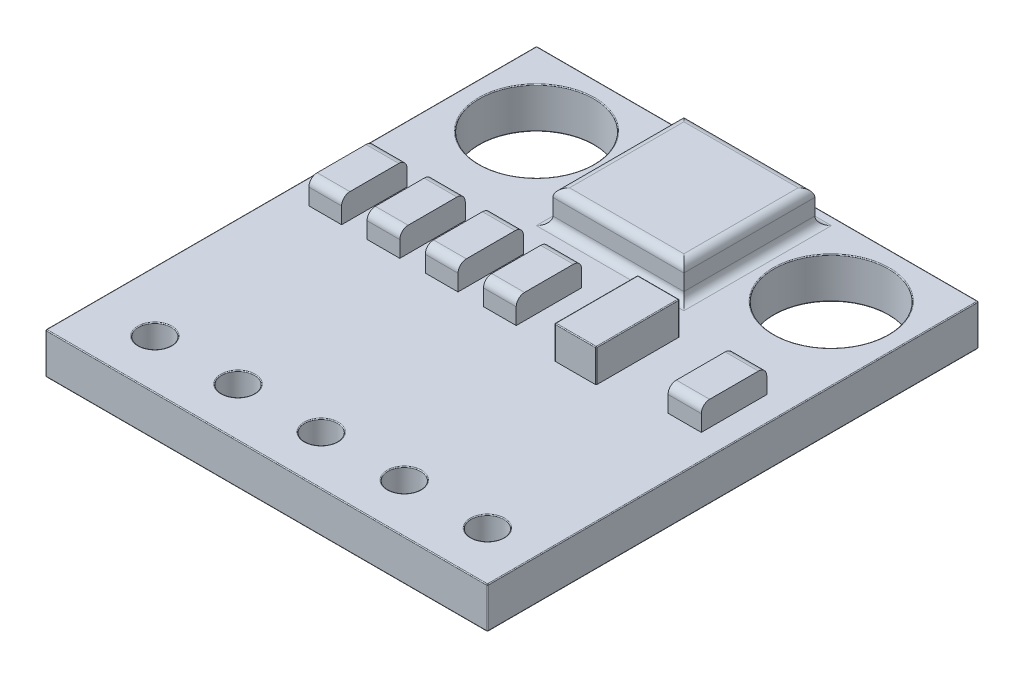
SolidWorks part; units mm, degrees
ref_plane "Front Plane" through (0, 0, 0) normal (0, 0, 1) x (1, 0, 0)
ref_plane "Top Plane" through (0, 0, 0) normal (0, 1, 0) x (1, 0, 0)
ref_plane "Right Plane" through (0, 0, 0) normal (1, 0, 0) x (0, 0, -1)
sketch "Sketch1" plane through (0, 0, 0) normal (0, 1, 0) x (1, 0, 0)
  line L1 (0, 0) -> (13.5, 0)
  line L2 (0, 0) -> (0, 15)
  line L3 (0, 15) -> (13.5, 15)
  line L4 (13.5, 0) -> (13.5, 15)
  dimension "D1" = 13.5
  dimension "D2" = 15
extrude "Boss-Extrude1" add sketch "Sketch1" along normal blind 1.25
sketch "Sketch2" plane through (0, 1.25, 0) normal (0, 1, 0) x (1, 0, 0)
  line L0 (0, 15) -> (0, 0) construction
  line L1 (5, 14.5) -> (9, 14.5)
  line L2 (5, 14.5) -> (5, 10.5)
  line L3 (5, 10.5) -> (9, 10.5)
  line L4 (9, 14.5) -> (9, 10.5)
  line L5 (13.5, 15) -> (0, 15) construction
  dimension "D1" = 4
  dimension "D2" = 4
  dimension "D3" = 5
  dimension "D4" = 0.5
extrude "Boss-Extrude2" add sketch "Sketch2" along normal blind 1
sketch "Sketch3" plane through (0, 1.25, 0) normal (0, 1, 0) x (1, 0, 0)
  line L0 (13.5, 0) -> (13.5, 15) construction
  line L1 (13.5, 15) -> (0, 15) construction
  line L2 (0, 15) -> (0, 0) construction
  circle A0 centre (11.25, 12.75) radius 1.75
  circle A1 centre (2.25, 12.75) radius 1.75
  dimension "D1" = 3.5
  dimension "D2" = 3.5
  dimension "D4" = 2.25
  dimension "D5" = 2.25
  dimension "D6" = 2.25
  dimension "D3" = 2.25
extrude "Cut-Extrude1" cut sketch "Sketch3" against normal blind 25.4
sketch "Sketch4" plane through (0, 1.25, 0) normal (0, 1, 0) x (1, 0, 0)
  line L0 (0, 15) -> (0, 0) construction
  line L1 (0.75, 9.2947) -> (1.75, 9.2947)
  line L2 (0.75, 9.2947) -> (0.75, 7.2947)
  line L3 (0.75, 7.2947) -> (1.75, 7.2947)
  line L4 (1.75, 9.2947) -> (1.75, 7.2947)
  line L5 (2.528, 9.2947) -> (3.528, 9.2947)
  line L6 (3.528, 9.2947) -> (3.528, 7.2947)
  line L7 (2.528, 7.2947) -> (3.528, 7.2947)
  line L8 (2.528, 9.2947) -> (2.528, 7.2947)
  line L9 (4.306, 9.2947) -> (5.306, 9.2947)
  line L10 (5.306, 9.2947) -> (5.306, 7.2947)
  line L11 (4.306, 7.2947) -> (5.306, 7.2947)
  line L12 (4.306, 9.2947) -> (4.306, 7.2947)
  line L13 (6.084, 9.2947) -> (7.084, 9.2947)
  line L14 (7.084, 9.2947) -> (7.084, 7.2947)
  line L15 (6.084, 7.2947) -> (7.084, 7.2947)
  line L16 (6.084, 9.2947) -> (6.084, 7.2947)
  line L17 (13.5, 0) -> (13.5, 15) construction
  line L18 (11.722, 9.2947) -> (12.738, 9.2947)
  line L19 (11.722, 9.2947) -> (11.722, 7.2947)
  line L20 (11.722, 7.2947) -> (12.738, 7.2947)
  line L21 (12.738, 9.2947) -> (12.738, 7.2947)
  dimension "D1" = 2
  dimension "D2" = 1
  dimension "D3" = 0.75
  dimension "D5" = 0.762
  dimension "D6" = 1.016
  dimension "D4" = 4
extrude "Boss-Extrude4" add sketch "Sketch4" along normal blind 0.75
sketch "Sketch5" plane through (0, 1.25, 0) normal (0, 1, 0) x (1, 0, 0)
  line L0 (7.084, 7.2947) -> (7.084, 9.2947) construction
  line L1 (8.608, 9.4836) -> (9.878, 9.4836)
  line L2 (8.608, 9.4836) -> (8.608, 6.9436)
  line L3 (8.608, 6.9436) -> (9.878, 6.9436)
  line L4 (9.878, 9.4836) -> (9.878, 6.9436)
  dimension "D1" = 1.27
  dimension "D2" = 2.54
  dimension "D3" = 1.524
extrude "Boss-Extrude5" add sketch "Sketch5" along normal blind 1
sketch "Sketch6" plane through (0, 1.25, 0) normal (0, 1, 0) x (1, 0, 0)
  line L0 (0, 0) -> (13.5, 0) construction
  line L1 (13.5, 0) -> (13.5, 15) construction
  circle A0 centre (12, 1.5) radius 0.5
  circle A1 centre (9.46, 1.5) radius 0.5
  circle A2 centre (6.92, 1.5) radius 0.5
  circle A3 centre (4.38, 1.5) radius 0.5
  circle A4 centre (1.84, 1.5) radius 0.5
  dimension "D1" = 1.5
  dimension "D2" = 1.5
  dimension "D3" = 5
extrude "Cut-Extrude2" cut sketch "Sketch6" against normal blind 25.4
fillet "Fillet1" radius 0.0254 4 edges at (11.25, 1.25, -11) (2.25, 1.25, -11) (11.25, 0, -14.5) (2.25, 0, -14.5)
fillet "Fillet2" radius 0.0254 10 edges at (1.84, 1.25, -1) (4.38, 1.25, -1) (6.92, 1.25, -1) (9.46, 1.25, -1) (12, 1.25, -1) (1.84, 0, -2) (4.38, 0, -2) (6.92, 0, -2) (9.46, 0, -2) (12, 0, -2)
fillet "Fillet3" radius 0.254 10 edges at (12.23, 2, -9.2947) (12.23, 2, -7.2947) (6.584, 2, -7.2947) (6.584, 2, -9.2947) (3.028, 2, -9.2947) (4.806, 2, -9.2947) (4.806, 2, -7.2947) (3.028, 2, -7.2947) (1.25, 2, -9.2947) (1.25, 2, -7.2947)
fillet "Fillet4" radius 0.254 8 edges at (9, 2.25, -12.5) (7, 2.25, -14.5) (5, 2.25, -12.5) (7, 2.25, -10.5) (7, 1.25, -10.5) (5, 1.25, -12.5) (7, 1.25, -14.5) (9, 1.25, -12.5)
fillet "Fillet5" radius 0.0254 8 edges at (8.608, 1.75, -6.9436) (8.608, 1.75, -9.4836) (9.878, 1.75, -9.4836) (9.878, 1.75, -6.9436) (9.243, 2.25, -9.4836) (8.608, 2.25, -8.2136) (9.243, 2.25, -6.9436) (9.878, 2.25, -8.2136)
fillet "Fillet6" radius 0.0254 12 edges at (6.75, 1.25, -15) (6.75, 0, -15) (0, 0.625, -15) (0, 1.25, -7.5) (0, 0, -7.5) (0, 0.625, 0) (6.75, 1.25, 0) (6.75, 0, 0) (13.5, 0.625, 0) (13.5, 1.25, -7.5) (13.5, 0.625, -15) (13.5, 0, -7.5)
